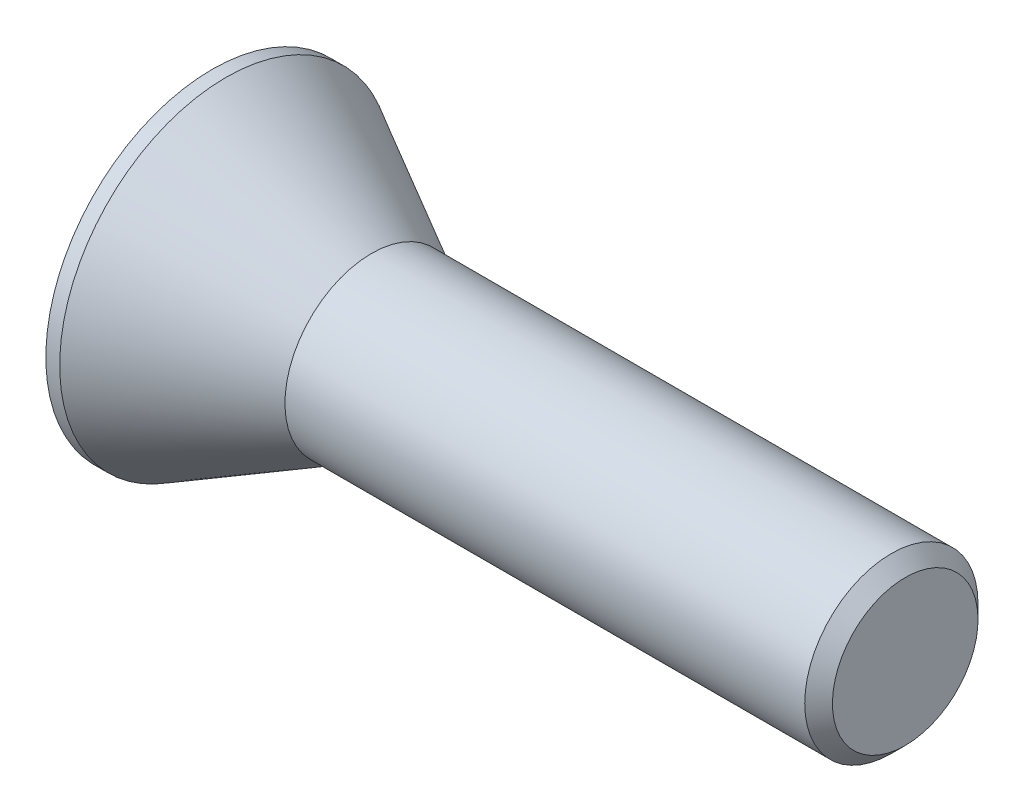
SolidWorks part; units mm, degrees
material "铸造碳钢"
ref_plane "前视基准面" through (0, 0, 0) normal (0, 0, 1) x (1, 0, 0)
ref_plane "上视基准面" through (0, 0, 0) normal (0, 1, 0) x (1, 0, 0)
ref_plane "右视基准面" through (0, 0, 0) normal (1, 0, 0) x (0, 0, -1)
other "Configuration Table"
sketch "草图1" plane through (0, 0, 0) normal (0, 0, 1) x (1, 0, 0)
  line L0 (0, 0) -> (0, -2.4)
  line L1 (0, -2.4) -> (0.2, -2.4)
  line L2 (0.2, -2.4) -> (2.3, -1.25)
  line L3 (2.3, -1.25) -> (10, -1.25)
  line L4 (10, -1.25) -> (10, 0)
  line L5 (10, 0) -> (0, 0)
  dimension "D1" = 1.25
  dimension "D2" = 2.4
  dimension "D3" = 2.3
  dimension "D4" = 10
  dimension "D5" = 0.2
revolve "旋转1" add sketch "草图1" angle 360 about L5
sketch "草图2" plane through (0, 0, 0) normal (-1, 0, 0) x (0, 0, 1)
  line L0 (0, 0) -> (2.4, 0) construction
  line L1 (0.866, 0) -> (0.433, 0.75)
  line L2 (0.433, 0.75) -> (-0.433, 0.75)
  line L3 (-0.433, 0.75) -> (-0.866, 0)
  line L4 (-0.866, 0) -> (-0.433, -0.75)
  line L5 (-0.433, -0.75) -> (0.433, -0.75)
  line L6 (0.433, -0.75) -> (0.866, 0)
  circle A0 centre (0, 0) radius 0.75 construction
  circle A1 centre (0, 0) radius 2.4 construction
  dimension "D1" = 1.5
  dimension "D2" = 60
extrude "切除-拉伸1" cut sketch "草图2" against normal blind 0.4
chamfer "倒角1" distance 0.2 angle 45 1 edges at (10, 1.25, 0)
